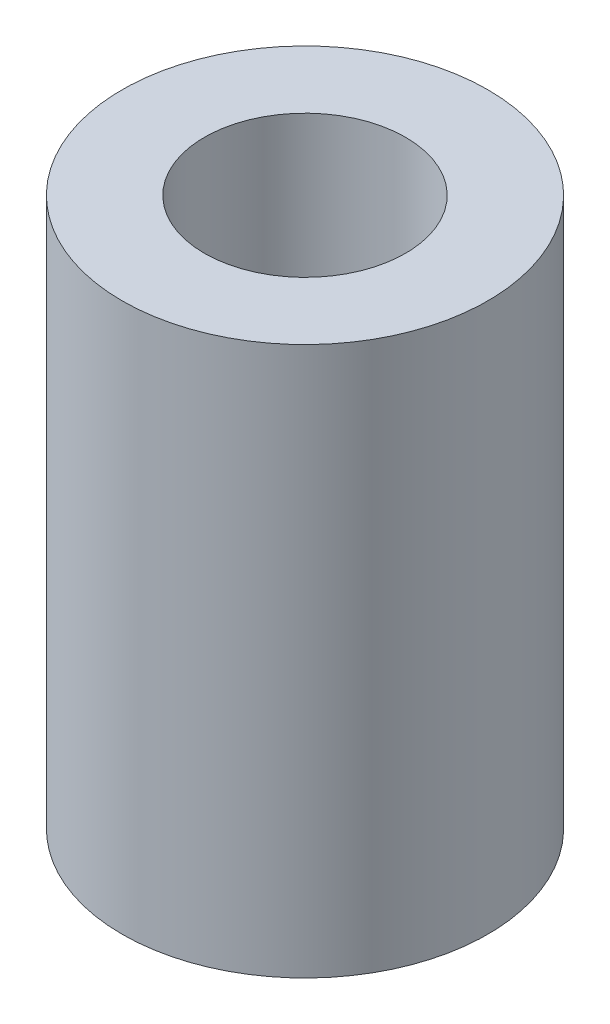
SolidWorks part; units mm, degrees
ref_plane "Front Plane" through (0, 0, 0) normal (0, 0, 1) x (1, 0, 0)
ref_plane "Top Plane" through (0, 0, 0) normal (0, 1, 0) x (1, 0, 0)
ref_plane "Right Plane" through (0, 0, 0) normal (1, 0, 0) x (0, 0, -1)
sketch "Sketch1" plane through (0, 0, 0) normal (0, 1, 0) x (1, 0, 0)
  circle A0 centre (0, 0) radius 1.65
  circle A1 centre (0, 0) radius 3
  dimension "D1" = 3.3
  dimension "D2" = 6
extrude "Boss-Extrude1" add sketch "Sketch1" along normal blind 9
